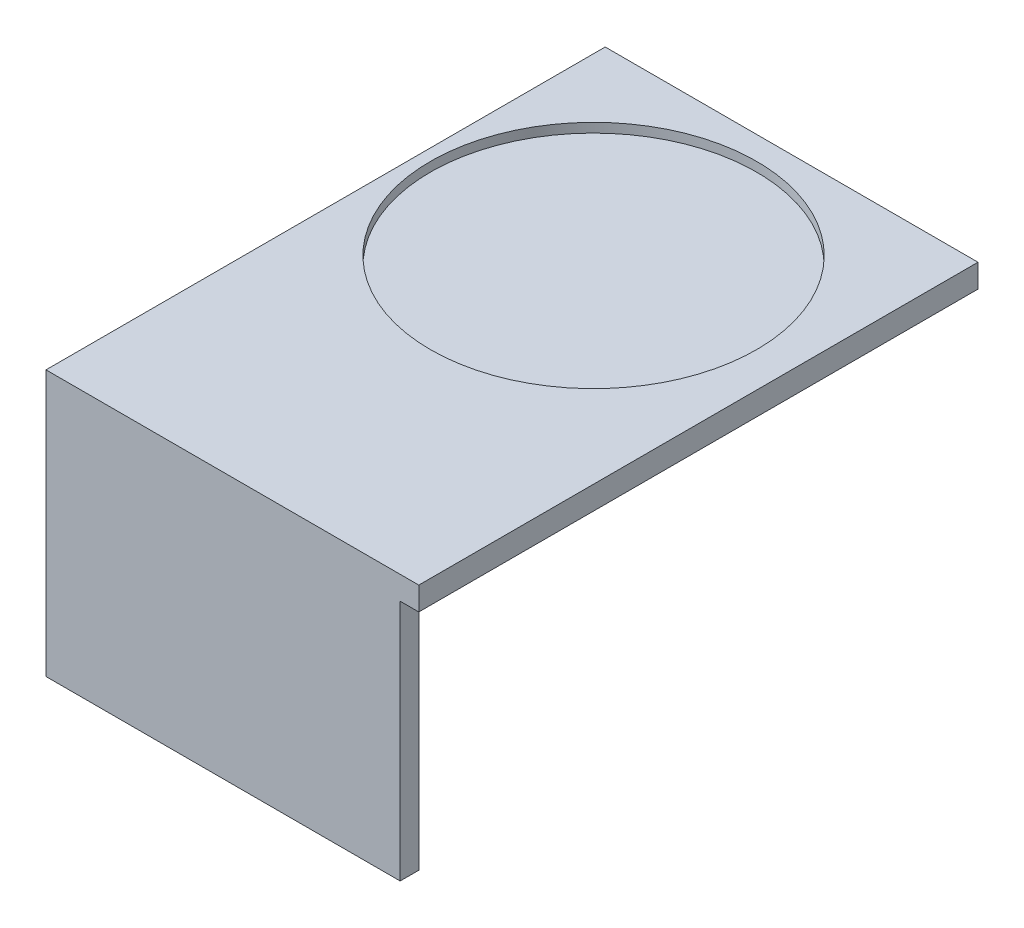
SolidWorks part; units mm, degrees
ref_plane "Front Plane" through (0, 0, 0) normal (0, 0, 1) x (1, 0, 0)
ref_plane "Top Plane" through (0, 0, 0) normal (0, 1, 0) x (1, 0, 0)
ref_plane "Right Plane" through (0, 0, 0) normal (1, 0, 0) x (0, 0, -1)
sketch "Sketch1" plane through (0, 0, 0) normal (0, 1, 0) x (1, 0, 0)
  line L0 (-37.5, 80) -> (42.5, 80) construction
  line L1 (-37.5, 80) -> (42.5, 80)
  line L2 (-37.5, 80) -> (-37.5, -40)
  line L3 (-37.5, -40) -> (42.5, -40)
  line L4 (42.5, 80) -> (42.5, -40)
  line L5 (42.5, 80) -> (42.5, -40) construction
  line L6 (42.5, -40) -> (38.5, -40) construction
  line L7 (-37.5, -40) -> (-37.5, 4) construction
extrude "Boss-Extrude1" add sketch "Sketch1" along normal blind 5 contours L1 L4 L3 L2
sketch "Sketch2" plane through (0, 0, 0) normal (0, -1, 0) x (1, 0, 0)
  line L0 (-37.5, 40) -> (38.5, 40)
  line L1 (-37.5, 40) -> (42.5, 40) construction
  line L2 (38.5, 40) -> (38.5, 36)
  line L3 (38.5, 36) -> (-37.5, 36)
  line L4 (-37.5, -80) -> (-37.5, 40) construction
  line L5 (-37.5, 36) -> (-37.5, 40)
  line L6 (42.5, -80) -> (42.5, 40) construction
  dimension "D1" = 4
  dimension "D2" = 4
extrude "Boss-Extrude2" add sketch "Sketch2" along normal blind 52
sketch "Sketch4" plane through (-37.5, 0, 0) normal (-1, 0, 0) x (0, 0, 1)
  line L0 (-30, 0) -> (-20, 0)
  line L1 (-80, 0) -> (36, 0) construction
  line L2 (-20, 0) -> (-20, -5)
  line L3 (-30, 0) -> (-30, -5)
  line L4 (36, -52) -> (36, 0) construction
  line L5 (-2, 9.6588) -> (-2, -8.7683) construction
  line L7 (16, 0) -> (16, -5)
  line L8 (26, 0) -> (16, 0)
  line L9 (-40, 199) -> (-40, -46) construction
  line L10 (19.4892, -9.7663) -> (36, -15)
  line L11 (36, -15) -> (36, 0)
  line L12 (36, 0) -> (26, 0)
  arc A0 (-30, -5) -> (-20, -5) centre (-25, -5) ccw
  circle A1 centre (-25, -5) radius 3.41
  circle A2 centre (21, -5) radius 3.41
  arc A3 (19.4892, -9.7663) -> (16, -5) centre (21, -5) cw
  dimension "D3" = 6.82
  dimension "D4" = 5
  dimension "D1" = 10
  dimension "D2" = 5
  dimension "D5" = 38
  dimension "D6" = 15
extrude "Boss-Extrude3" add sketch "Sketch4" against normal blind 4
sketch "Sketch5" plane through (0, 5, 0) normal (0, 1, 0) x (1, 0, 0)
  circle A0 centre (0, 40) radius 35
  dimension "D1" = 70
extrude "Cut-Extrude1" cut sketch "Sketch5" against normal blind 2
equation "\"Printed Hole Size\"= 6.5"
equation "\"CAD Hole Size\"= 0.9683 * \"Printed Hole Size\" + 0.5265"
